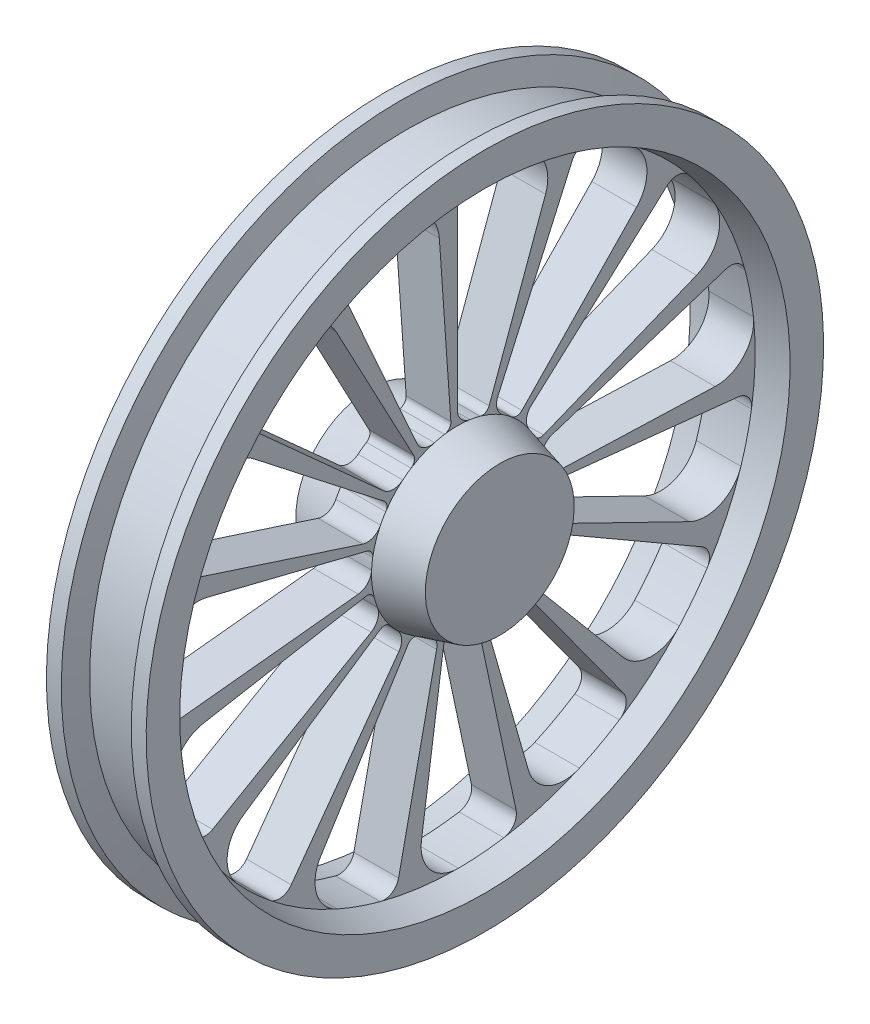
SolidWorks part; units mm, degrees
material "1060 Alloy"
ref_plane "Front Plane" through (0, 0, 0) normal (0, 0, 1) x (1, 0, 0)
ref_plane "Top Plane" through (0, 0, 0) normal (0, 1, 0) x (1, 0, 0)
ref_plane "Right Plane" through (0, 0, 0) normal (1, 0, 0) x (0, 0, -1)
sketch "Sketch1" plane through (0, 0, 0) normal (0, 0, 1) x (1, 0, 0)
  line L0 (0, 0) -> (-87, 0)
  line L1 (-87, 0) -> (-87, 100)
  line L2 (-87, 100) -> (-30, 115.2731)
  line L3 (-30, 115.2731) -> (-30, 400.0859)
  line L4 (-30, 400.0859) -> (-67, 410)
  line L5 (-67, 410) -> (-67, 455)
  line L6 (-67, 455) -> (-47, 455)
  line L7 (-47, 455) -> (-38.9615, 425)
  line L8 (-38.9615, 425) -> (0, 425)
  line L9 (0, 425) -> (0, 0)
  line L10 (-87, 100) -> (-16.0431, 100) construction
  line L11 (-67, 410) -> (-15.6398, 410) construction
  dimension "D1" = 100
  dimension "D2" = 15
  dimension "D3" = 30
  dimension "D4" = 455
  dimension "D5" = 67
  dimension "D6" = 20
  dimension "D7" = 30
  dimension "D8" = 45
  dimension "D9" = 15
  dimension "D10" = 87
revolve "Revolve1" add sketch "Sketch1" angle 360 about L0
mirror "Mirror1" about plane through (0, 425, 0) normal (1, 0, 0) of "Revolve1"
sketch "Sketch2" plane through (30, 0, 0) normal (1, 0, 0) x (0, 0, -1)
  line L0 (0, 115.9608) -> (0, 50115.9608) construction
  line L1 (0, 0) -> (17101.0072, 46984.631) construction
  line L2 (0, 0) -> (20336.8322, 45677.2729) construction
  line L3 (0, 133.7864) -> (0, 379.5593)
  line L4 (42.7092, 117.3426) -> (118.5089, 325.6006)
  arc A0 (21.0524, 399.5316) -> (81.7395, 391.647) centre (0, 0) cw
  circle A1 centre (0, 0) radius 115.2731 construction
  circle A2 centre (0, 0) radius 400.0859 construction
  arc A3 (30.6531, 111.1228) -> (17.043, 114.0062) centre (0, 0) ccw
  arc A4 (0, 379.5593) -> (21.0524, 399.5316) centre (20, 379.5593) cw
  arc A5 (81.7395, 391.647) -> (118.5089, 325.6006) centre (71.5243, 342.7016) cw
  arc A6 (17.043, 114.0062) -> (0, 133.7864) centre (20, 133.7864) cw
  arc A7 (42.7092, 117.3426) -> (30.6531, 111.1228) centre (33.3123, 120.7628) cw
  point P18 (0, 400.0859)
  point P21 (136.8374, 375.9577)
  point P24 (0, 115.2731)
  point P27 (39.4257, 108.3213)
  dimension "D3" = 20
  dimension "D4" = 50
  dimension "D5" = 20
  dimension "D6" = 10
  dimension "D1" = 20
  dimension "D2" = 4
extrude "Cut-Extrude1" cut sketch "Sketch2" against normal through all both and the other way through all
pattern_circular "CirPattern1" count 15 over 360 about axis through (0, 0, 0) along (1, 0, 0) of "Cut-Extrude1"
